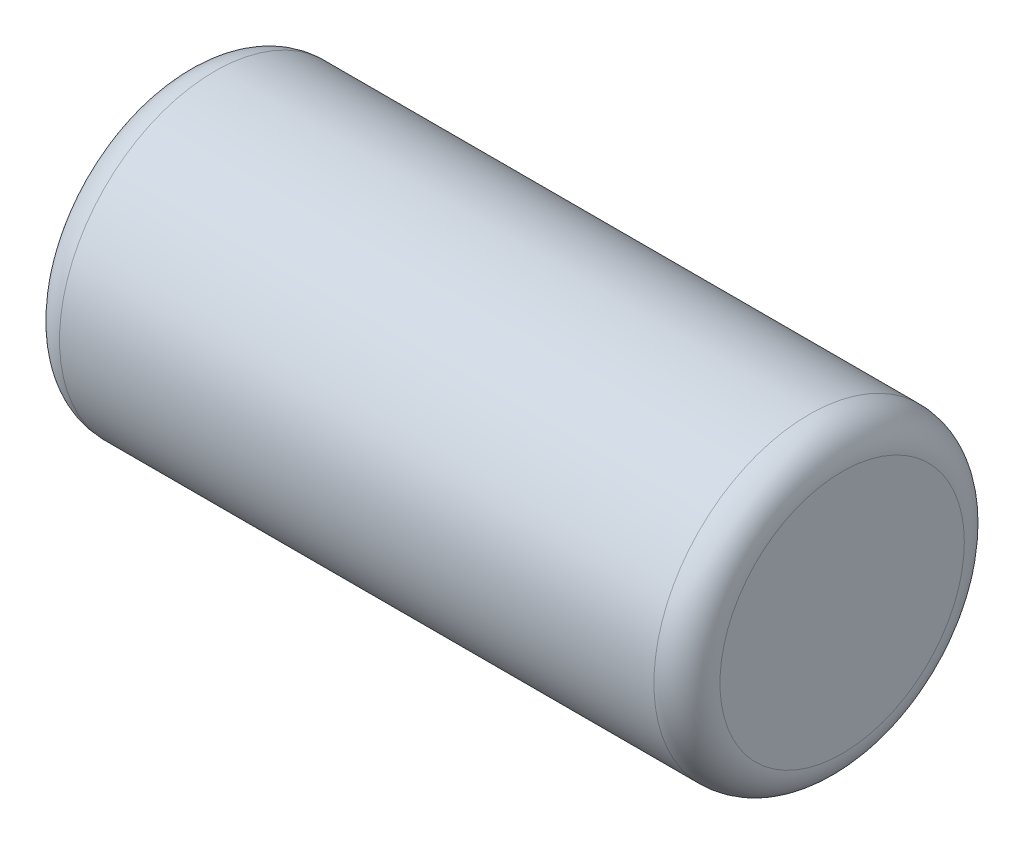
SolidWorks part; units mm, degrees
ref_plane "Alzado" through (0, 0, 0) normal (1, 0, 0) x (0, 1, 0)
ref_plane "Planta" through (0, 0, 0) normal (0, 0, 1) x (0, 1, 0)
ref_plane "Vista lateral" through (0, 0, 0) normal (0, 1, 0) x (-1, 0, 0)
sketch "Croquis1" plane through (0, 0, 0) normal (1, 0, 0) x (0, 1, 0)
  circle A0 centre (0, 0) radius 2.35
  dimension "D1" = 4.7
extrude "Saliente-Extruir1" add sketch "Croquis1" along normal blind 10
fillet "Redondeo1" radius 0.5 2 edges at (0, 0, -2.35) (10, 0, -2.35)
